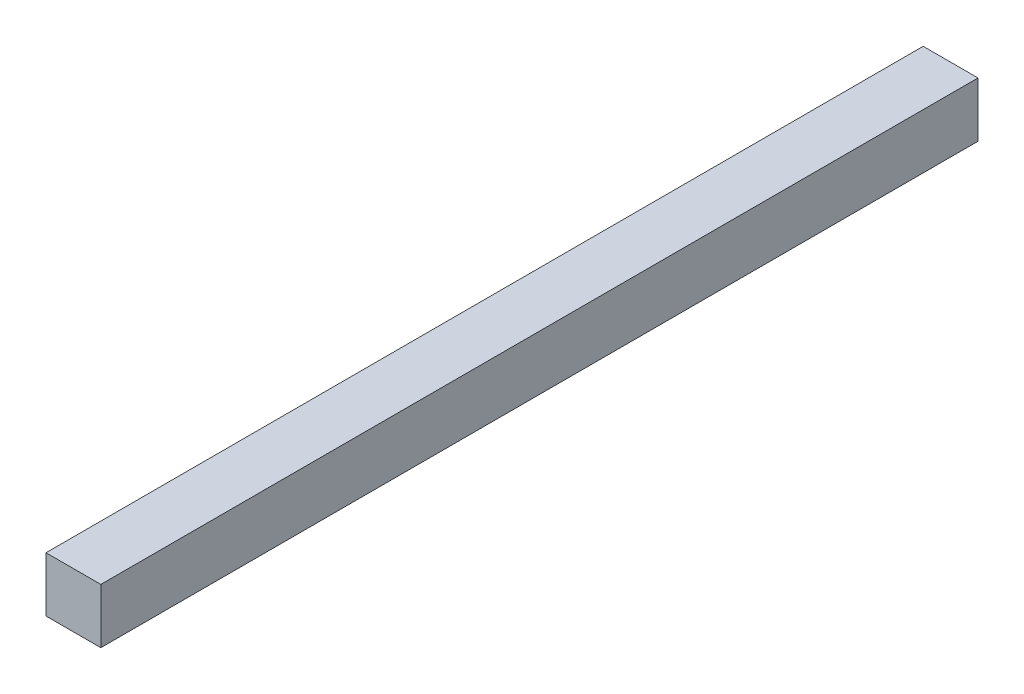
SolidWorks part; units mm, degrees
material "2024 Alloy"
ref_plane "Front Plane" through (0, 0, 0) normal (0, 0, 1) x (1, 0, 0)
ref_plane "Top Plane" through (0, 0, 0) normal (0, 1, 0) x (1, 0, 0)
ref_plane "Right Plane" through (0, 0, 0) normal (1, 0, 0) x (0, 0, -1)
sketch "Sketch1" plane through (0, 0, 0) normal (0, 0, 1) x (1, 0, 0)
  line L1 (-12.7, 12.7) -> (12.7, 12.7)
  line L2 (-12.7, 12.7) -> (-12.7, -12.7)
  line L3 (-12.7, -12.7) -> (12.7, -12.7)
  line L4 (12.7, 12.7) -> (12.7, -12.7)
  line L5 (-12.7, 12.7) -> (12.7, -12.7) construction
  line L6 (-12.7, -12.7) -> (12.7, 12.7) construction
  point P4 (0, 0)
  dimension "D1" = 25.4
  dimension "D2" = 25.4
extrude "Boss-Extrude1" add sketch "Sketch1" along normal blind 406.4 contours L1 L4 L3 L2
